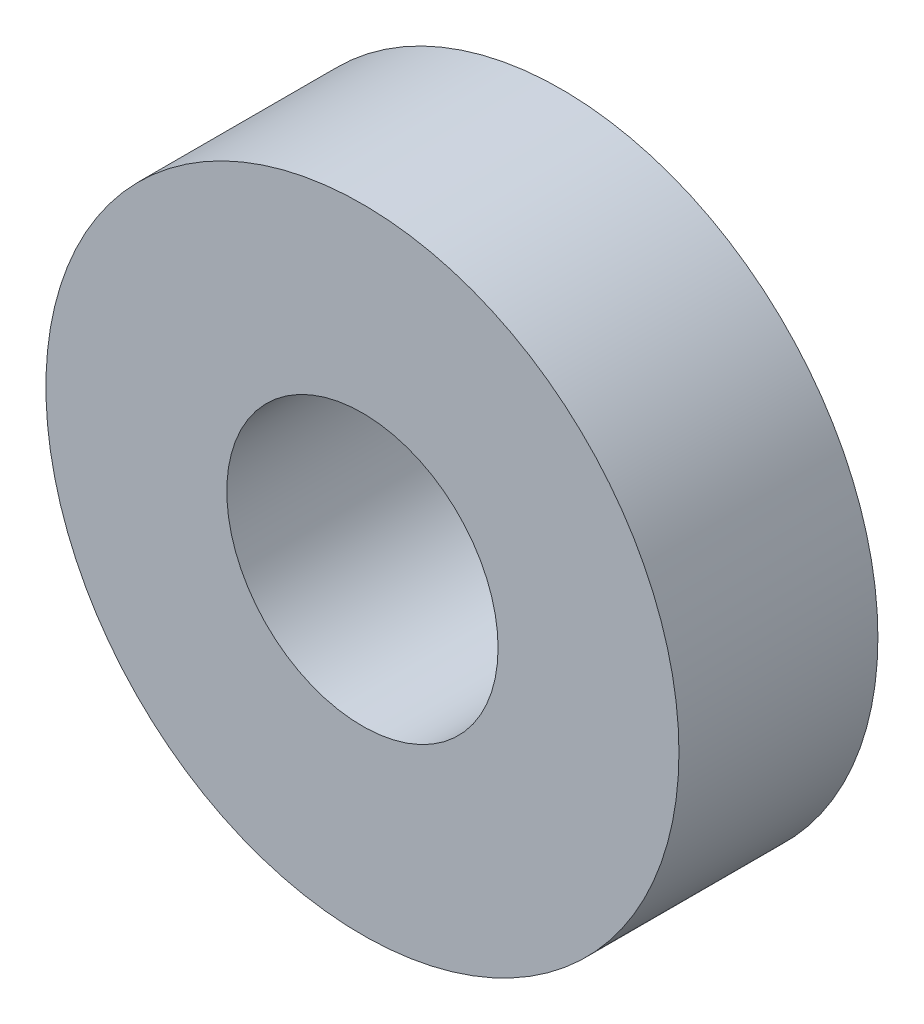
SolidWorks part; units mm, degrees
ref_plane "Front Plane" through (0, 0, 0) normal (0, 0, 1) x (1, 0, 0)
ref_plane "Top Plane" through (0, 0, 0) normal (0, 1, 0) x (1, 0, 0)
ref_plane "Right Plane" through (0, 0, 0) normal (1, 0, 0) x (0, 0, -1)
sketch "Sketch1" plane through (0, 0, 0) normal (0, 0, 1) x (1, 0, 0)
  circle A0 centre (0, 0) radius 7.5
  circle A1 centre (0, 0) radius 17.5
  dimension "D1" = 15
  dimension "D2" = 35
extrude "Boss-Extrude1" add sketch "Sketch1" along normal blind 11
